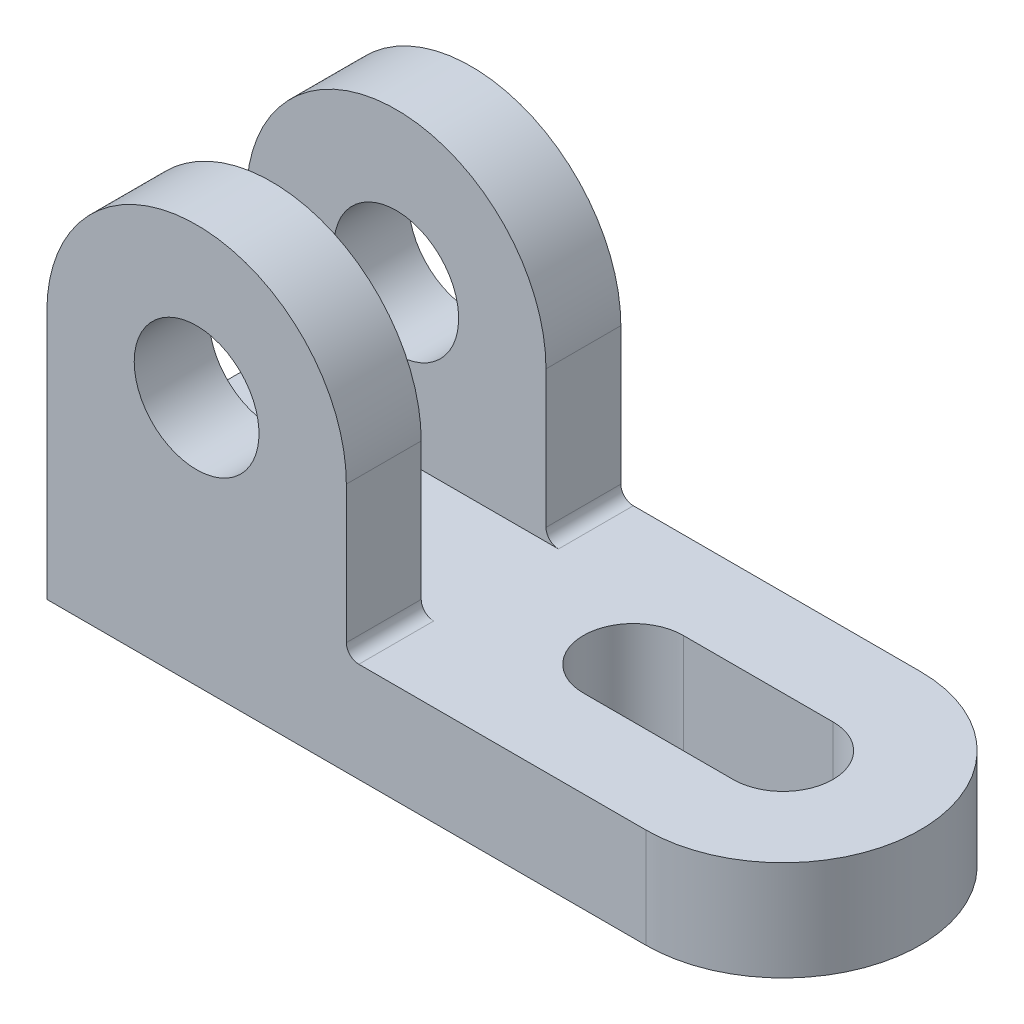
SolidWorks part; units mm, degrees
ref_plane "Front Plane" through (0, 0, 0) normal (0, 0, 1) x (1, 0, 0)
ref_plane "Top Plane" through (0, 0, 0) normal (0, 1, 0) x (1, 0, 0)
ref_plane "Right Plane" through (0, 0, 0) normal (1, 0, 0) x (0, 0, -1)
sketch "Sketch1" plane through (0, 0, 0) normal (0, 1, 0) x (1, 0, 0)
  line L0 (48, 0) -> (24, 0) construction
  line L1 (-48, 22) -> (48, 22)
  line L2 (-48, 22) -> (-48, -22)
  line L3 (-48, -22) -> (48, -22)
  line L5 (-48, 22) -> (48, -22) construction
  line L6 (-48, -22) -> (48, 22) construction
  line L7 (48, -8) -> (24, -8)
  line L8 (48, 8) -> (24, 8)
  arc A0 (48, -22) -> (48, 22) centre (48, 0) ccw
  arc A1 (48, -8) -> (48, 8) centre (48, 0) ccw
  arc A2 (24, 8) -> (24, -8) centre (24, 0) ccw
  point P0 (0, 0)
  point P8 (36, 0)
  dimension "D1" = 96
extrude "Boss-Extrude1" add sketch "Sketch1" along normal blind 16
sketch "Sketch3" plane through (0, 0, 22) normal (0, 0, 1) x (1, 0, 0)
  line L0 (2, 16) -> (0, 16)
  line L1 (-48, 16) -> (0, 16)
  line L2 (-48, 16) -> (-48, 40)
  line L4 (0, 18) -> (0, 40)
  arc A0 (0, 18) -> (2, 16) centre (2, 18) ccw
  arc A1 (0, 40) -> (-48, 40) centre (-24, 40) ccw
  dimension "D1" = 24
extrude "Boss-Extrude2" add sketch "Sketch3" against normal blind 12
sketch "Sketch7" plane through (0, 0, -22) normal (0, 0, -1) x (-1, 0, 0)
  line L0 (0, 16) -> (-2, 16)
  line L1 (48, 16) -> (0, 16)
  line L2 (48, 16) -> (48, 40)
  line L4 (0, 18) -> (0, 40)
  arc A0 (48, 40) -> (0, 40) centre (24, 40) ccw
  arc A1 (0, 18) -> (-2, 16) centre (-2, 18) cw
  dimension "D1" = 2
extrude "Boss-Extrude4" add sketch "Sketch7" against normal blind 12
sketch "Sketch9" plane through (0, 0, -22) normal (0, 0, -1) x (-1, 0, 0)
  circle A0 centre (24, 40) radius 10
  dimension "D1" = 20
extrude "Cut-Extrude1" cut sketch "Sketch9" against normal through all
